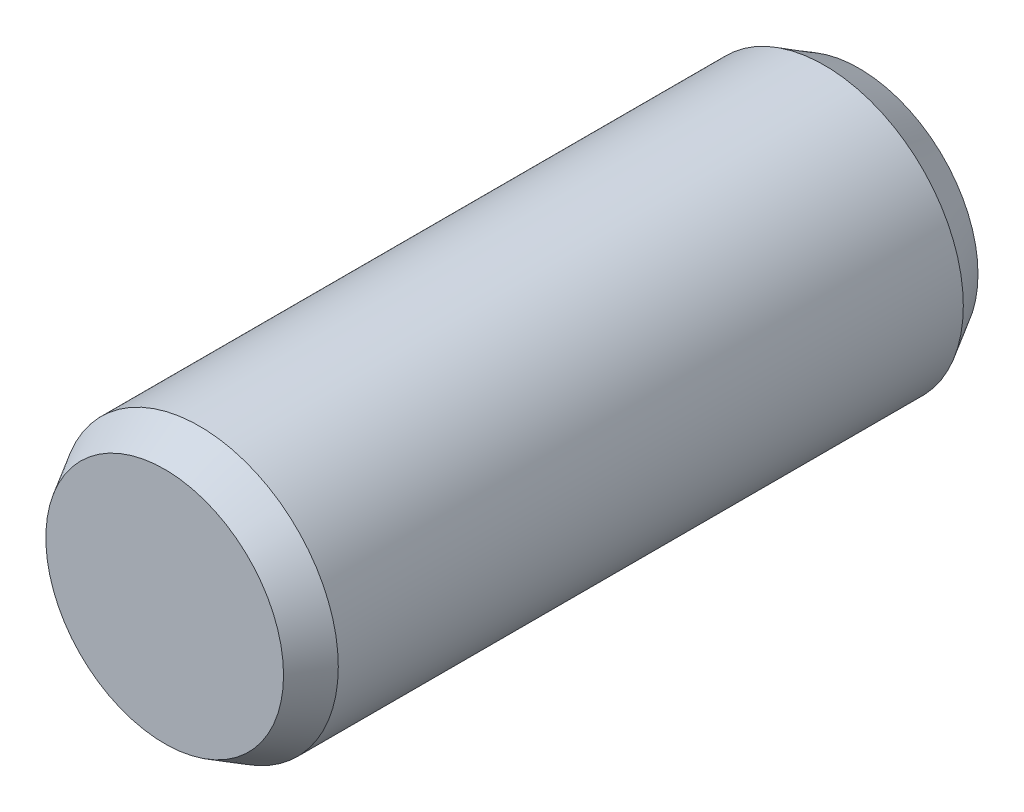
SolidWorks part; units mm, degrees
material "Plain Carbon Steel"
ref_plane "Front" through (0, 0, 0) normal (0, 0, 1) x (1, 0, 0)
ref_plane "Base" through (0, 0, 0) normal (0, 1, 0) x (1, 0, 0)
ref_plane "Side" through (0, 0, 0) normal (1, 0, 0) x (0, 0, -1)
sketch "Sketch1" plane through (0, 0, 0) normal (0, 0, 1) x (1, 0, 0)
  line L2 (0, 0) -> (0, 2) construction
  circle A0 centre (0, 0) radius 2
  dimension "NOMDIA" = 4
extrude "Boss-Extrude1" add sketch "Sketch1" along normal blind 10
chamfer "Chamfer1" distance 0.5 angle 30 2 edges at (2, 0, 10) (2, 0, 0)
